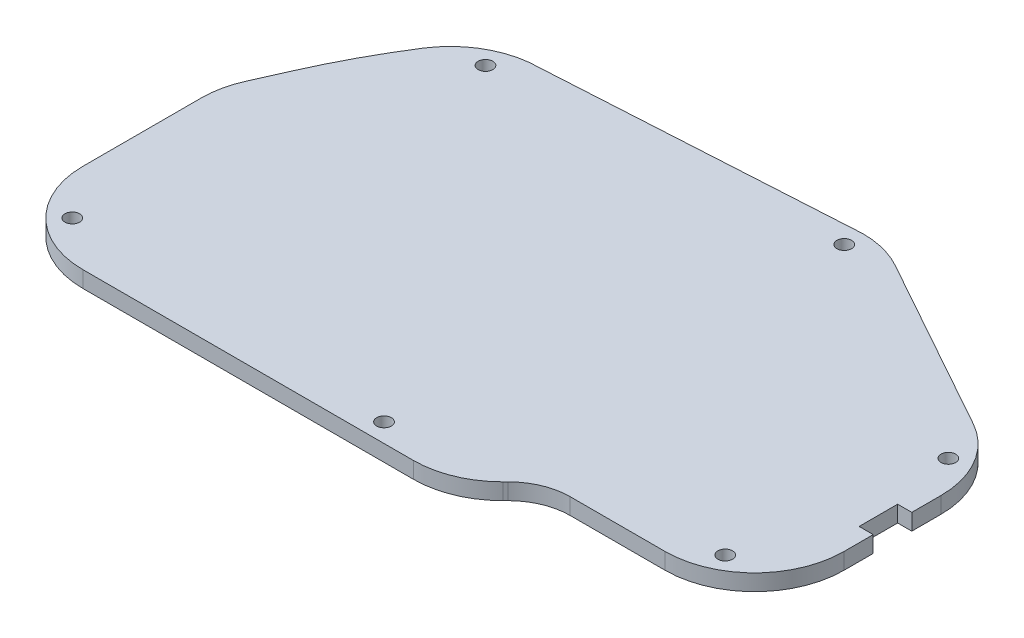
SolidWorks part; units mm, degrees
ref_plane "Front Plane" through (0, 0, 0) normal (0, 0, 1) x (1, 0, 0)
ref_plane "Top Plane" through (0, 0, 0) normal (0, 1, 0) x (1, 0, 0)
ref_plane "Right Plane" through (0, 0, 0) normal (1, 0, 0) x (0, 0, -1)
sketch "Sketch2" plane through (0, 0, 0) normal (0, 1, 0) x (1, 0, 0)
  line L7 (-257.8256, -105.63) -> (-193.4944, -105.63) construction
  line L8 (-181.1201, -100.5044) -> (-180.6101, -99.9944) construction
  line L9 (-172.1248, -96.4797) -> (-153.6496, -96.4797) construction
  line L10 (-136.1496, -78.9797) -> (-136.1496, -60.0821) construction
  line L11 (-145.1341, -44.7936) -> (-179.4485, -25.681) construction
  line L12 (-187.9639, -23.4695) -> (-247.3805, -26.968) construction
  line L13 (-271.0251, -51.648) -> (-273.8196, -57.9411) construction
  line L14 (-275.3256, -65.0434) -> (-275.3256, -88.13) construction
  line L15 (-145.1828, -44.881) -> (-179.4971, -25.7684)
  line L16 (-187.961, -23.5695) -> (-247.3776, -27.068)
  line L17 (-270.9337, -51.6886) -> (-273.7282, -57.9817)
  line L18 (-275.2256, -65.0434) -> (-275.2256, -88.13)
  line L19 (-257.8256, -105.53) -> (-193.4944, -105.53)
  line L20 (-181.1908, -100.4337) -> (-180.6808, -99.9237)
  line L21 (-172.1248, -96.3797) -> (-153.6496, -96.3797)
  line L22 (-136.2496, -78.9797) -> (-136.2496, -73.2809)
  line L23 (-136.2496, -69.5309) -> (-138.9996, -69.5309) construction
  line L24 (-138.9996, -65.7809) -> (-138.9996, -73.2809)
  line L25 (-138.9996, -65.7809) -> (-136.2496, -65.7809)
  line L26 (-138.9996, -73.2809) -> (-136.2496, -73.2809)
  line L27 (-136.2496, -78.9797) -> (-136.2496, -60.0821) construction
  line L28 (-136.2496, -65.7809) -> (-136.2496, -60.0821)
  line L29 (-136.2496, -65.7809) -> (-136.2496, -73.2809) construction
  circle A15 centre (-147.2076, -91.1273) radius 1.425
  circle A16 centre (-141.795, -53.1155) radius 1.425
  circle A17 centre (-187.9639, -27.2195) radius 1.425
  arc A18 (-275.3256, -88.13) -> (-257.8256, -105.63) centre (-257.8256, -88.13) ccw construction
  arc A19 (-193.4944, -105.63) -> (-181.1201, -100.5044) centre (-193.4944, -88.13) ccw construction
  arc A20 (-172.1248, -96.4797) -> (-180.6101, -99.9944) centre (-172.1248, -108.4797) ccw construction
  arc A21 (-153.6496, -96.4797) -> (-136.1496, -78.9797) centre (-153.6496, -78.9797) ccw construction
  arc A22 (-136.1496, -60.0821) -> (-145.1341, -44.7936) centre (-153.6496, -60.0821) ccw construction
  arc A23 (-179.4485, -25.681) -> (-187.9639, -23.4695) centre (-187.9639, -40.9695) ccw construction
  arc A24 (-247.3805, -26.968) -> (-262.1548, -35.0887) centre (-247.3805, -44.468) ccw construction
  arc A25 (-262.1548, -35.0887) -> (-271.0251, -51.648) centre (-154.7153, -103.2964) ccw construction
  arc A26 (-273.8196, -57.9411) -> (-275.3256, -65.0434) centre (-257.8256, -65.0434) ccw construction
  circle A27 centre (-253.0515, -31.942) radius 1.425
  circle A28 centre (-267.5484, -97.8527) radius 1.425
  circle A29 centre (-202.8547, -101.88) radius 1.425
  arc A30 (-179.4971, -25.7684) -> (-187.961, -23.5695) centre (-187.9639, -40.9695) ccw
  arc A31 (-247.3776, -27.068) -> (-262.0703, -35.1423) centre (-247.3805, -44.468) ccw
  arc A32 (-262.0703, -35.1423) -> (-270.9337, -51.6886) centre (-154.7153, -103.2964) ccw
  arc A33 (-273.7282, -57.9817) -> (-275.2256, -65.0434) centre (-257.8256, -65.0434) ccw
  arc A34 (-275.2256, -88.13) -> (-257.8256, -105.53) centre (-257.8256, -88.13) ccw
  arc A35 (-193.4944, -105.53) -> (-181.1908, -100.4337) centre (-193.4944, -88.13) ccw
  arc A36 (-172.1248, -96.3797) -> (-180.6808, -99.9237) centre (-172.1248, -108.4797) ccw
  arc A37 (-153.6496, -96.3797) -> (-136.2496, -78.9797) centre (-153.6496, -78.9797) ccw
  arc A38 (-136.2496, -60.0821) -> (-145.1828, -44.881) centre (-153.6496, -60.0821) ccw
  point P69 (-138.9996, -69.5309)
  dimension "D2" = 7.5
  dimension "D1" = 0.1
extrude "Boss-Extrude1" add sketch "Sketch2" along normal blind 3.175
